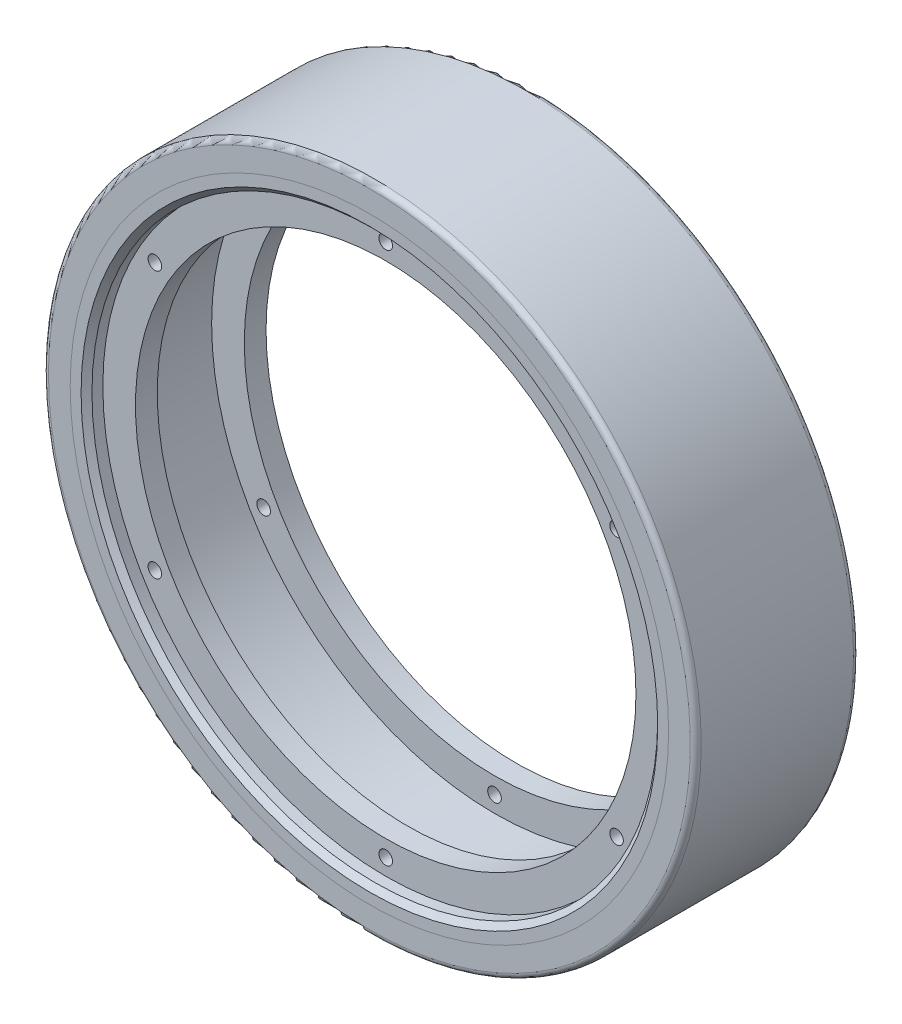
SolidWorks part; units mm, degrees
material "6061 合金"
ref_plane "前视基准面" through (0, 0, 0) normal (0, 0, 1) x (1, 0, 0)
ref_plane "上视基准面" through (0, 0, 0) normal (0, 1, 0) x (1, 0, 0)
ref_plane "右视基准面" through (0, 0, 0) normal (1, 0, 0) x (0, 0, -1)
other "Configuration Table"
sketch "草图1" plane through (0, 0, 0) normal (0, 0, 1) x (1, 0, 0)
  circle A0 centre (0, 0) radius 55
  dimension "D1" = 110
extrude "凸台-拉伸1" add sketch "草图1" along normal mid plane 30
sketch "草图2" plane through (0, 0, 15) normal (0, 0, 1) x (1, 0, 0)
  circle A0 centre (0, 0) radius 52
  circle A1 centre (0, 0) radius 55 construction
  dimension "D1" = 3
extrude "切除-拉伸1" cut sketch "草图2" against normal blind 3
mirror "镜向1" about plane through (0, 0, 0) normal (0, 0, 1) of "切除-拉伸1"
sketch "草图3" plane through (0, 0, -12) normal (0, 0, -1) x (-1, 0, 0)
  circle A0 centre (0, 0) radius 46
  circle A1 centre (0, 0) radius 52 construction
  dimension "D1" = 6
extrude "切除-拉伸2" cut sketch "草图3" against normal blind 194
sketch "草图4" plane through (0, 0, 0) normal (0, 0, 1) x (1, 0, 0)
  circle A0 centre (0, 0) radius 52 construction
  circle A1 centre (0, 0) radius 52
extrude "切除-拉伸3" cut sketch "草图4" against normal mid plane 16
sketch "草图5" plane through (0, 0, 12) normal (0, 0, 1) x (1, 0, 0)
  circle A0 centre (0, 0) radius 49 construction
  circle A1 centre (0, 0) radius 46 construction
  dimension "D1" = 3
hole_wizard "M3 螺纹孔1" positions "草图6" profile "草图7" tap size "M3" standard "GB" end condition through all
sketch "草图6" plane through (0, 0, 12) normal (0, 0, 1) x (1, 0, 0)
  line L0 (0, 49) -> (0, 0) construction
  circle A0 centre (0, 0) radius 49 construction
  point P0 (0, 49)
sketch "草图7" plane through (0, 49, 12) normal (1, 0, 0) x (0, -1, 0)
  line L0 (0, 0) -> (0, 27)
  line L1 (0, 27) -> (1.25, 27)
  line L2 (1.25, 27) -> (1.25, 0)
  line L5 (1.25, 0) -> (0, 0)
  line L11 (0, -6.35) -> (0, 107.95) construction
  dimension "通孔螺纹孔钻头直径" = 2.5
  dimension "通孔螺纹孔钻头深度" = 27
cosmetic thread "孔螺蚊线1" parameters "D2"=3
pattern_circular "阵列(圆周)1" count 6 over 360 about axis through (0, 0, 0) along (0, 0, 1) of "M3 螺纹孔1"
chamfer "倒角1" distance 1 angle 45 2 edges at (52, 0, -15) (52, 0, 15)
sketch "草图8" plane through (0, 0, -15) normal (0, 0, -1) x (-1, 0, 0)
  circle A0 centre (0, 0) radius 60
  circle A1 centre (0, 0) radius 55 construction
  circle A2 centre (0, 0) radius 55
  dimension "D1" = 5
extrude "凸台-拉伸2" add sketch "草图8" against normal blind 30 separate body contours A0
fillet "圆角2" radius 1 2 edges at (-60, 0, 15) (-60, 0, -15)
